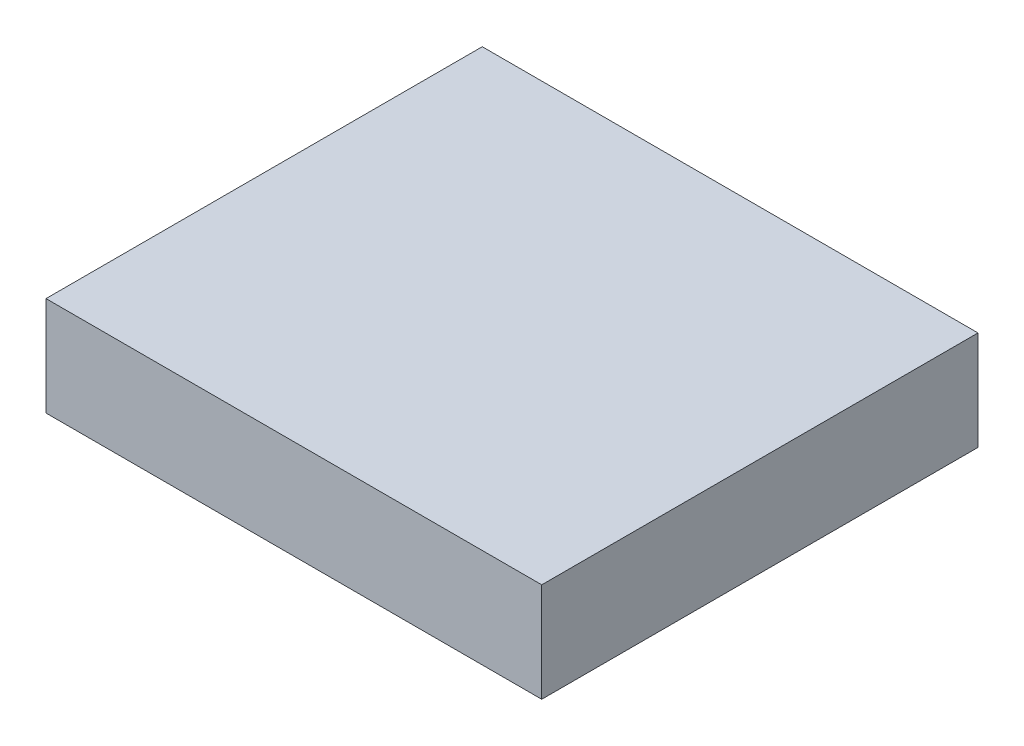
SolidWorks part; units mm, degrees
ref_plane "Front Plane" through (0, 0, 0) normal (0, 0, 1) x (1, 0, 0)
ref_plane "Top Plane" through (0, 0, 0) normal (0, 1, 0) x (1, 0, 0)
ref_plane "Right Plane" through (0, 0, 0) normal (1, 0, 0) x (0, 0, -1)
sketch "Sketch1" plane through (0, 0, 0) normal (0, 1, 0) x (1, 0, 0)
  line L1 (0, 0) -> (5, 0)
  line L2 (0, 0) -> (0, -4.4)
  line L3 (0, -4.4) -> (5, -4.4)
  line L4 (5, 0) -> (5, -4.4)
  dimension "D1" = 4.4
  dimension "D2" = 5
extrude "Boss-Extrude1" add sketch "Sketch1" along normal blind 1
